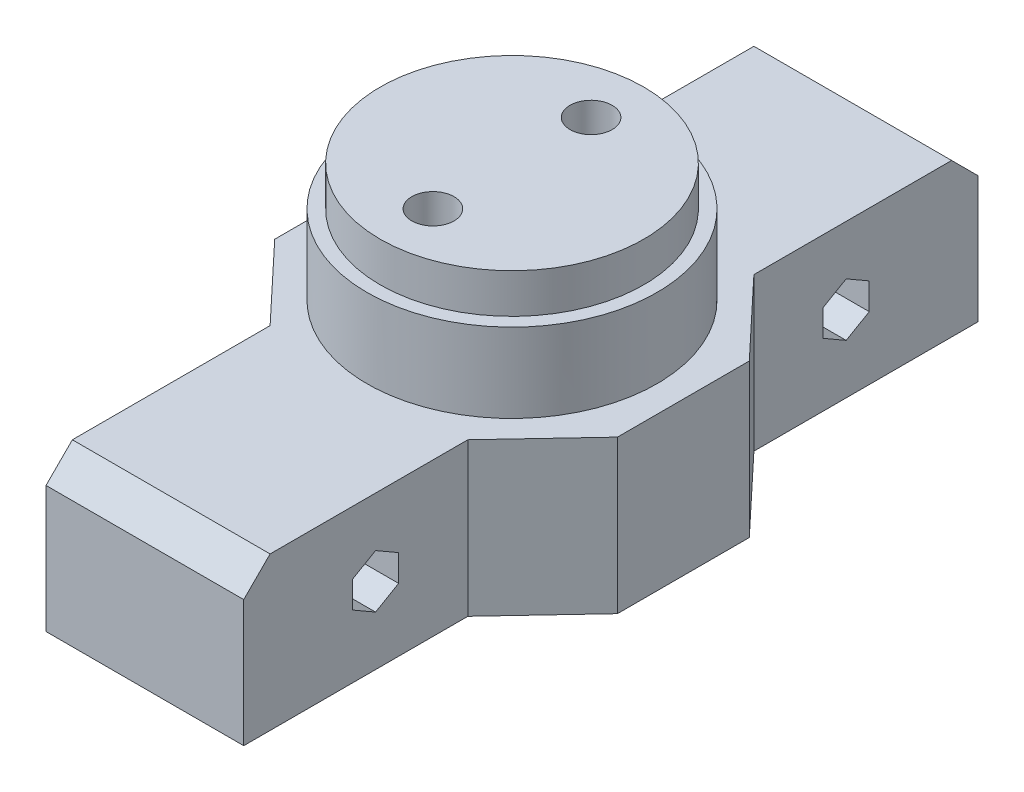
SolidWorks part; units mm, degrees
ref_plane "Plan de face" through (0, 0, 0) normal (0, 0, 1) x (1, 0, 0)
ref_plane "Plan de dessus" through (0, 0, 0) normal (0, 1, 0) x (1, 0, 0)
ref_plane "Plan de droite" through (0, 0, 0) normal (1, 0, 0) x (0, 0, -1)
sketch "Esquisse1" plane through (0, 0, 0) normal (0, 1, 0) x (1, 0, 0)
  line L0 (0, 0) -> (0, 27.85) construction
  line L1 (7.5, 27.85) -> (-7.5, 27.85)
  line L2 (-7.5, 27.85) -> (-7.5, 10.85)
  line L3 (-7.5, 10.85) -> (-13, 5)
  line L4 (-13, 5) -> (-13, -5)
  line L5 (0, 0) -> (26.7955, 0) construction
  line L6 (7.5, -27.85) -> (-7.5, -27.85)
  line L7 (-7.5, -10.85) -> (-13, -5)
  line L8 (-7.5, -27.85) -> (-7.5, -10.85)
  line L9 (7.5, -27.85) -> (7.5, -10.85)
  line L10 (7.5, -10.85) -> (13, -5)
  line L11 (13, 5) -> (13, -5)
  line L12 (7.5, 10.85) -> (13, 5)
  line L13 (7.5, 27.85) -> (7.5, 10.85)
  point P15 (-13, 0)
  point P21 (0, -27.85)
  point P24 (13, 0)
  dimension "D1" = 15
  dimension "D2" = 17
  dimension "D3" = 55.7
  dimension "D4" = 26
  dimension "D5" = 5
extrude "Boss.-Extru.1" add sketch "Esquisse1" along normal blind 11.6
sketch "Esquisse2" plane through (0, 11.6, 0) normal (0, 1, 0) x (1, 0, 0)
  circle A0 centre (0, 0) radius 10
  dimension "D1" = 20
extrude "Boss.-Extru.2" add sketch "Esquisse2" along normal blind 9
sketch "Esquisse3" plane through (0, 0, 0) normal (0, -1, 0) x (1, 0, 0)
  circle A0 centre (0, 0) radius 6 construction
  circle A1 centre (0, 6) radius 1.6
  circle A2 centre (0, -6) radius 1.6
  dimension "D1" = 12
  dimension "D2" = 3.2
  dimension "D3" = 2
extrude "Enlèv. mat.-Extru.1" cut sketch "Esquisse3" against normal through all both and the other way through all
sketch "Esquisse6" plane through (-7.5, 0, 0) normal (-1, 0, 0) x (0, 0, 1)
  line L0 (-27.85, 11.6) -> (-27.85, 0) construction
  line L1 (0, 0) -> (0, -11.3746) construction
  line L2 (16.1, 6.8104) -> (17.85, 7.8207)
  line L3 (-17.85, 7.8207) -> (-19.6, 6.8104)
  line L4 (-19.6, 6.8104) -> (-19.6, 4.7896)
  line L5 (-19.6, 4.7896) -> (-17.85, 3.7793)
  line L6 (-17.85, 3.7793) -> (-16.1, 4.7896)
  line L7 (-16.1, 4.7896) -> (-16.1, 6.8104)
  line L8 (-16.1, 6.8104) -> (-17.85, 7.8207)
  line L9 (16.1, 4.7896) -> (16.1, 6.8104)
  line L10 (17.85, 3.7793) -> (16.1, 4.7896)
  line L11 (19.6, 4.7896) -> (17.85, 3.7793)
  line L12 (19.6, 6.8104) -> (19.6, 4.7896)
  line L13 (17.85, 7.8207) -> (19.6, 6.8104)
  circle A2 centre (-17.85, 5.8) radius 1.75 construction
  point P4 (-27.85, 5.8)
  dimension "D2" = 10
  dimension "D3" = 3.5
extrude "Enlèv. mat.-Extru.2" cut sketch "Esquisse6" against normal through all both and the other way through all
chamfer "Chanfrein1" distance 2 angle 45 2 edges at (0, 11.6, 27.85) (0, 11.6, -27.85)
sketch "Esquisse7" plane through (0, 11.6, 0) normal (0, 1, 0) x (1, 0, 0)
  circle A0 centre (0, 0) radius 11
  circle A1 centre (0, 6) radius 1.6 construction
  circle A3 centre (0, -6) radius 1.6 construction
  circle A4 centre (0, 6) radius 1.6
  circle A6 centre (0, -6) radius 1.6
  dimension "D1" = 22
extrude "Boss.-Extru.3" add sketch "Esquisse7" along normal blind 6
sketch "Esquisse8" plane through (0, 0, 0) normal (0, -1, 0) x (1, 0, 0)
  line L1 (0, 9.2332) -> (-2.8, 7.6166)
  line L2 (-2.8, 7.6166) -> (-2.8, 4.3834)
  line L3 (-2.8, 4.3834) -> (0, 2.7668)
  line L4 (0, 2.7668) -> (2.8, 4.3834)
  line L5 (2.8, 4.3834) -> (2.8, 7.6166)
  line L6 (2.8, 7.6166) -> (0, 9.2332)
  circle A0 centre (0, 6) radius 2.8 construction
  dimension "D1" = 5.6
extrude "Enlèv. mat.-Extru.3" cut sketch "Esquisse8" against normal blind 10
pattern_circular "Répétition circulaire1" count 2 over 360 about axis through (0, 0, 0) along (0, 1, 0) of "Enlèv. mat.-Extru.3"
